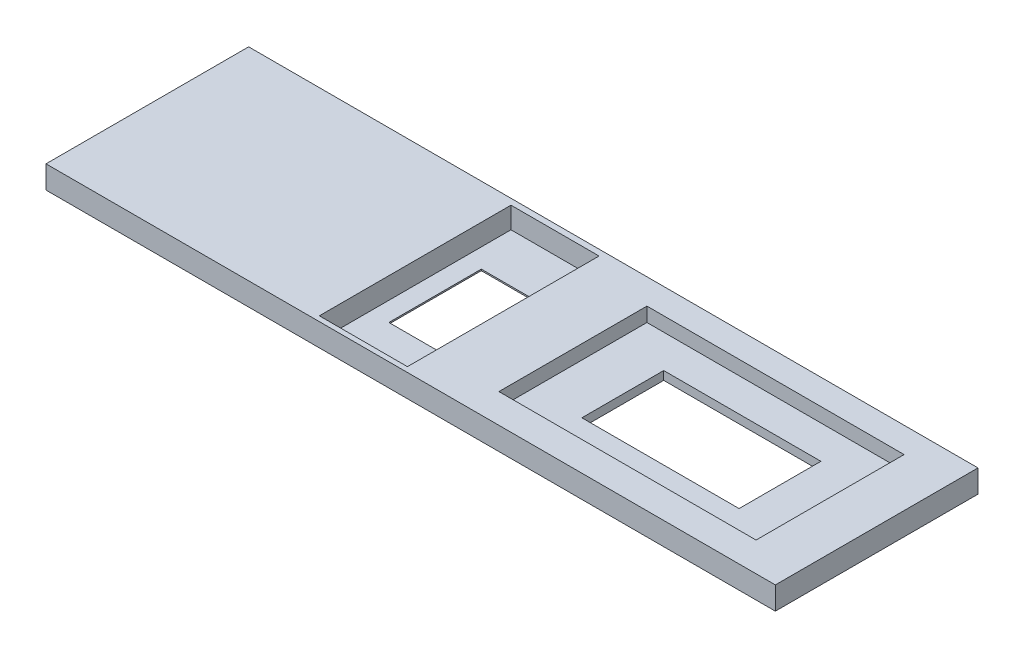
SolidWorks part; units mm, degrees
material "PLA"
ref_plane "Front Plane" through (0, 0, 0) normal (0, 0, 1) x (1, 0, 0)
ref_plane "Top Plane" through (0, 0, 0) normal (0, 1, 0) x (1, 0, 0)
ref_plane "Right Plane" through (0, 0, 0) normal (1, 0, 0) x (0, 0, -1)
sketch "Sketch1" plane through (0, 0, 0) normal (0, 1, 0) x (1, 0, 0)
  line L0 (-55, 0) -> (55, 0) construction
  line L1 (-256.4, 71.4) -> (256.4, 71.4)
  line L2 (-256.4, 71.4) -> (-256.4, -71.08)
  line L3 (-256.4, -71.08) -> (256.4, -71.08)
  line L4 (256.4, 71.4) -> (256.4, -71.08)
  line L5 (0, -55) -> (0, 55) construction
  dimension "D1" = 142.48
  dimension "D2" = 512.8
  dimension "D3" = 71.4
  dimension "D4" = 256.4
extrude "Boss-Extrude1" add sketch "Sketch1" along normal blind 16 contours L4 L3 L2 L1
sketch "Sketch5" plane through (0, 16, 0) normal (0, 1, 0) x (1, 0, 0)
  line L1 (41.49, 53.54) -> (222.3, 53.54)
  line L2 (41.49, 53.54) -> (41.49, -50.54)
  line L3 (41.49, -50.54) -> (222.3, -50.54)
  line L4 (222.3, 53.54) -> (222.3, -50.54)
  line L6 (256.4, 71.4) -> (256.4, -71.08) construction
  dimension "D1" = 180.81
  dimension "D2" = 34.1
  dimension "D3" = 104.08
sketch "Sketch6" plane through (0, 16, 0) normal (0, 1, 0) x (1, 0, 0)
  line L0 (41.49, 53.54) -> (41.49, -50.54) construction
  line L1 (76.625, 30.2) -> (187.165, 30.2)
  line L2 (76.625, 30.2) -> (76.625, -27.34)
  line L3 (76.625, -27.34) -> (187.165, -27.34)
  line L4 (187.165, 30.2) -> (187.165, -27.34)
  line L7 (41.49, 53.54) -> (222.3, 53.54) construction
  dimension "D1" = 110.54
  dimension "D2" = 57.54
  dimension "D3" = 35.135
  dimension "D4" = 23.34
extrude "Cut-Extrude2" cut sketch "Sketch5" against normal blind 10 contours L2 L3 L4 L1
extrude "Cut-Extrude3" cut sketch "Sketch6" against normal through all contours L3 L4 L1 L2
sketch "Sketch7" plane through (0, 16, 0) normal (0, 1, 0) x (1, 0, 0)
  line L0 (-256.4, 71.4) -> (-256.4, -71.08) construction
  line L1 (-5.83, -67.53) -> (-67.76, -67.53)
  line L2 (-5.83, -67.53) -> (-5.83, 67.2)
  line L3 (-5.83, 67.2) -> (-67.76, 67.2)
  line L4 (-67.76, -67.53) -> (-67.76, 67.2)
  dimension "D1" = 61.93
  dimension "D2" = 188.64
  dimension "D3" = 134.73
extrude "Cut-Extrude4" cut sketch "Sketch7" against normal blind 15 contours L4 L3 L2 L1
sketch "Sketch8" plane through (0, 1, 0) normal (0, 1, 0) x (1, 0, 0)
  line L0 (-67.76, -67.53) -> (-67.76, 67.2) construction
  line L1 (-19.26, -32.1508) -> (-54.26, -32.1508)
  line L2 (-19.26, -32.1508) -> (-19.26, 32.8492)
  line L3 (-19.26, 32.8492) -> (-54.26, 32.8492)
  line L4 (-54.26, -32.1508) -> (-54.26, 32.8492)
  dimension "D1" = 35
  dimension "D2" = 13.5
  dimension "D3" = 65
extrude "Cut-Extrude5" cut sketch "Sketch8" against normal blind 5
